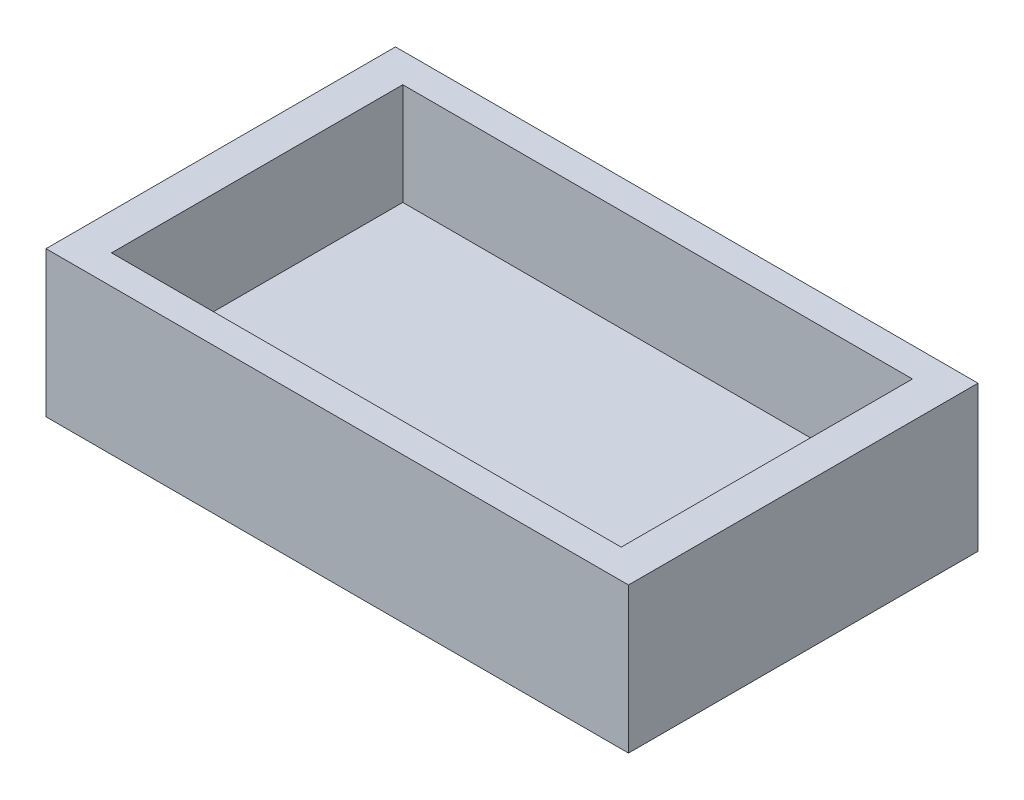
SolidWorks part; units mm, degrees
ref_plane "Front Plane" through (0, 0, 0) normal (0, 0, 1) x (1, 0, 0)
ref_plane "Top Plane" through (0, 0, 0) normal (0, 1, 0) x (1, 0, 0)
ref_plane "Right Plane" through (0, 0, 0) normal (1, 0, 0) x (0, 0, -1)
sketch "Sketch2" plane through (0, 0, 0) normal (0, 1, 0) x (1, 0, 0)
  line L1 (-20, 12) -> (20, 12)
  line L2 (-20, 12) -> (-20, -12)
  line L3 (-20, -12) -> (20, -12)
  line L4 (20, 12) -> (20, -12)
  line L5 (-20, 12) -> (20, -12) construction
  line L6 (-20, -12) -> (20, 12) construction
  point P0 (0, 0)
extrude "Boss-Extrude1" add sketch "Sketch2" along normal blind 10
sketch "Sketch3" plane through (0, 10, 0) normal (0, 1, 0) x (1, 0, 0)
  line L1 (-17.5, 10) -> (17.5, 10)
  line L2 (-17.5, 10) -> (-17.5, -10)
  line L3 (-17.5, -10) -> (17.5, -10)
  line L4 (17.5, 10) -> (17.5, -10)
  line L5 (-17.5, 10) -> (17.5, -10) construction
  line L6 (-17.5, -10) -> (17.5, 10) construction
  point P0 (0, 0)
extrude "Cut-Extrude1" cut sketch "Sketch3" against normal blind 7
ref_plane "Plane4" through (0, -10, 0) normal (0, -1, 0) x (-1, 0, 0)
sketch "Sketch6" plane through (0, -10, 0) normal (0, -1, 0) x (-1, 0, 0)
  point P0 (0, 0)
sketch "Sketch9" plane through (0, 0, 0) normal (0, -1, 0) x (1, 0, 0)
  line L1 (20, -12) -> (-20, -12)
  line L2 (20, -12) -> (20, 12)
  line L3 (20, 12) -> (-20, 12)
  line L4 (-20, -12) -> (-20, 12)
  line L5 (20, -12) -> (-20, 12) construction
  line L6 (20, 12) -> (-20, -12) construction
  point P0 (0, 0)
loft "Loft1" add profiles "Sketch9", "Sketch6"
